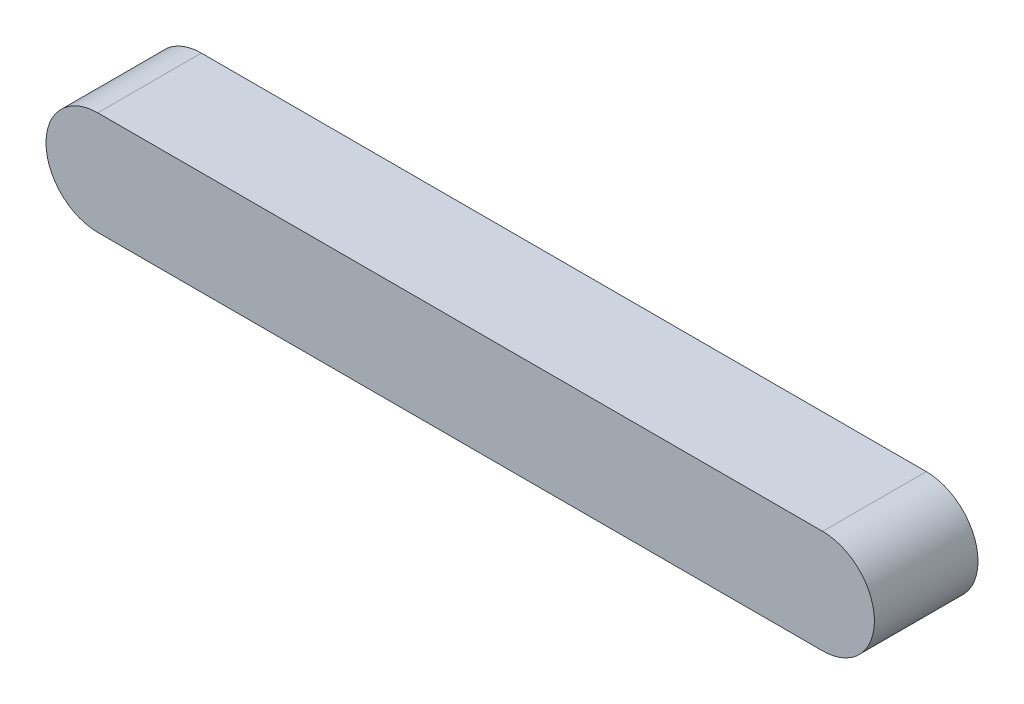
SolidWorks part; units mm, degrees
ref_plane "Front Plane" through (0, 0, 0) normal (0, 0, 1) x (1, 0, 0)
ref_plane "Top Plane" through (0, 0, 0) normal (0, 1, 0) x (1, 0, 0)
ref_plane "Right Plane" through (0, 0, 0) normal (1, 0, 0) x (0, 0, -1)
sketch "Sketch1" plane through (0, 0, 0) normal (0, 0, 1) x (1, 0, 0)
  line L1 (0, 0) -> (177.8, 0)
  line L2 (0, 0) -> (0, 25.4)
  line L3 (0, 25.4) -> (177.8, 25.4)
  line L4 (177.8, 0) -> (177.8, 25.4)
  circle A0 centre (0, 12.7) radius 12.7
  circle A1 centre (177.8, 12.7) radius 12.7
  dimension "D1" = 25.4
  dimension "D2" = 177.8
extrude "Boss-Extrude1" add sketch "Sketch1" along normal blind 25.4 contours L2 A0 | L2 A0 | A1 L3 A0 L1 | L4 A1 | L4 A1
